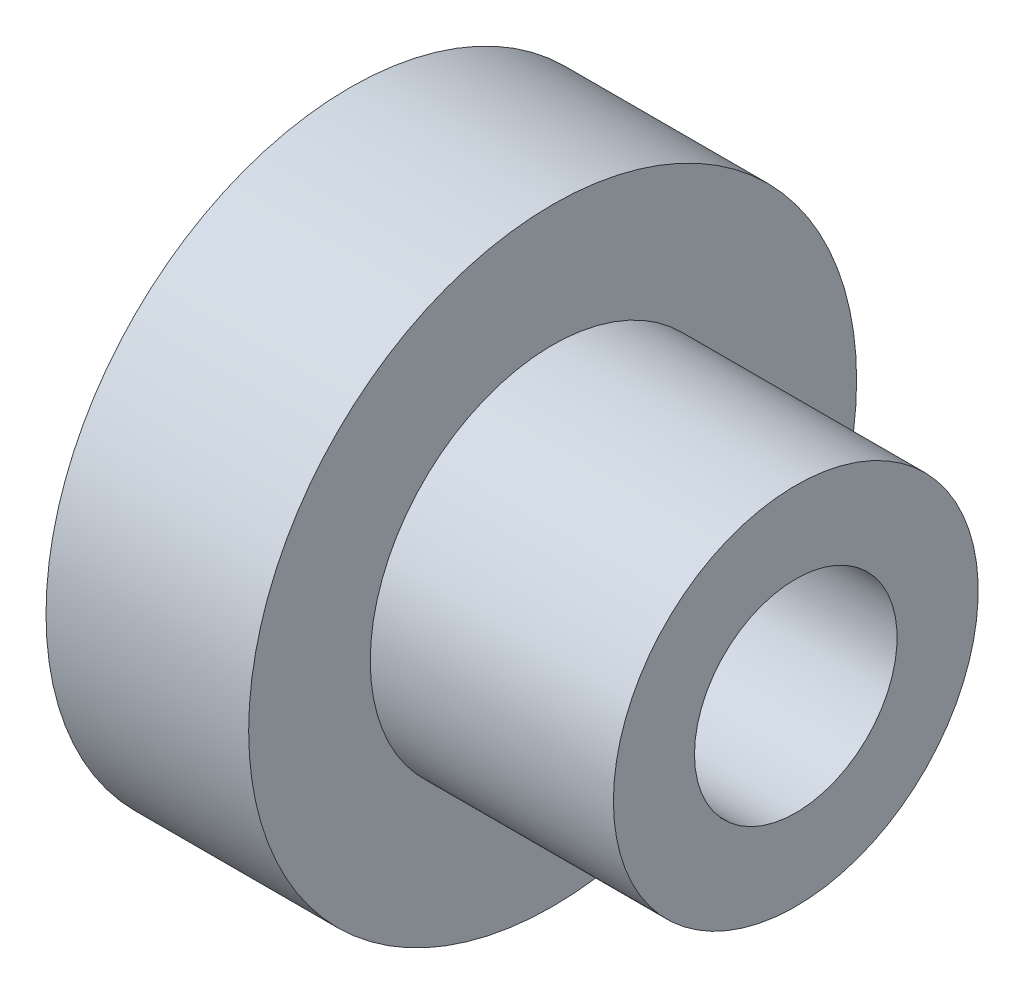
SolidWorks part; units mm, degrees
ref_plane "Front Plane" through (0, 0, 0) normal (0, 0, 1) x (1, 0, 0)
ref_plane "Top Plane" through (0, 0, 0) normal (0, 1, 0) x (1, 0, 0)
ref_plane "Right Plane" through (0, 0, 0) normal (1, 0, 0) x (0, 0, -1)
sketch "Sketch1" plane through (0, 0, 0) normal (0, 0, 1) x (1, 0, 0)
  line L0 (0, 0) -> (17.2507, 0) construction
  line L1 (0, 2.5) -> (0, 7.5)
  line L2 (0, 7.5) -> (5, 7.5)
  line L3 (5, 7.5) -> (5, 4.5)
  line L4 (5, 4.5) -> (11, 4.5)
  line L5 (11, 4.5) -> (11, 2.5)
  line L6 (11, 2.5) -> (0, 2.5)
  dimension "D1" = 2.5
  dimension "D2" = 7.5
  dimension "D3" = 5
  dimension "D4" = 4.5
  dimension "D5" = 11
revolve "Revolve1" add sketch "Sketch1" angle 360 about L0
